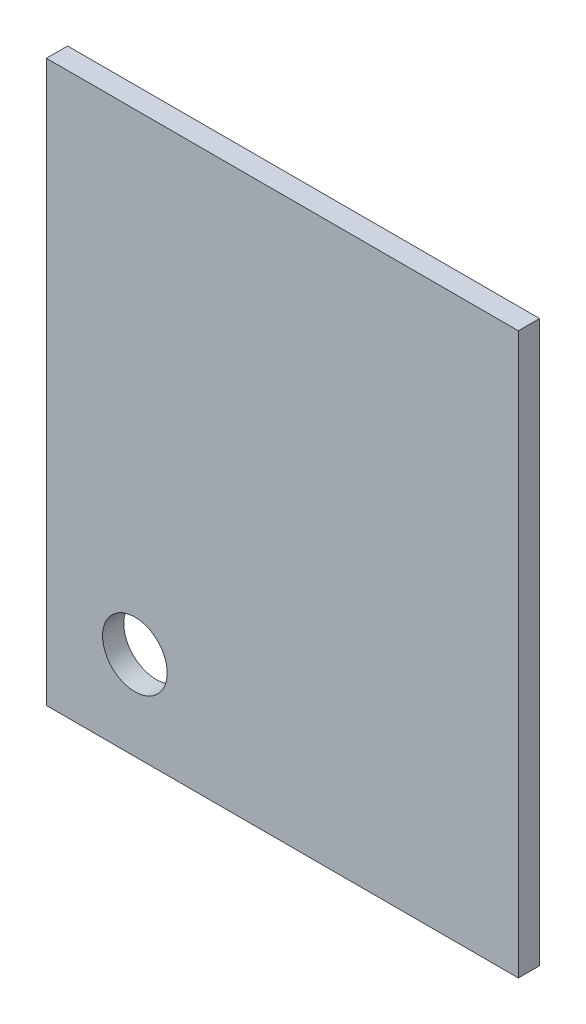
SolidWorks part; units mm, degrees
ref_plane "Front Plane" through (0, 0, 0) normal (0, 0, 1) x (1, 0, 0)
ref_plane "Top Plane" through (0, 0, 0) normal (0, 1, 0) x (1, 0, 0)
ref_plane "Right Plane" through (0, 0, 0) normal (1, 0, 0) x (0, 0, -1)
sketch "Sketch1" plane through (0, 0, 0) normal (0, 0, 1) x (1, 0, 0)
  line L1 (0, 0) -> (50.8, 0)
  line L2 (0, 0) -> (0, 60.325)
  line L3 (0, 60.325) -> (50.8, 60.325)
  line L4 (50.8, 0) -> (50.8, 60.325)
  circle A0 centre (9.525, 9.525) radius 3.4801
  dimension "D1" = 9.525
  dimension "D3" = 50.8
  dimension "D4" = 60.325
  dimension "D2" = 9.525
extrude "Extrude2" add sketch "Sketch1" against normal blind 2.286
